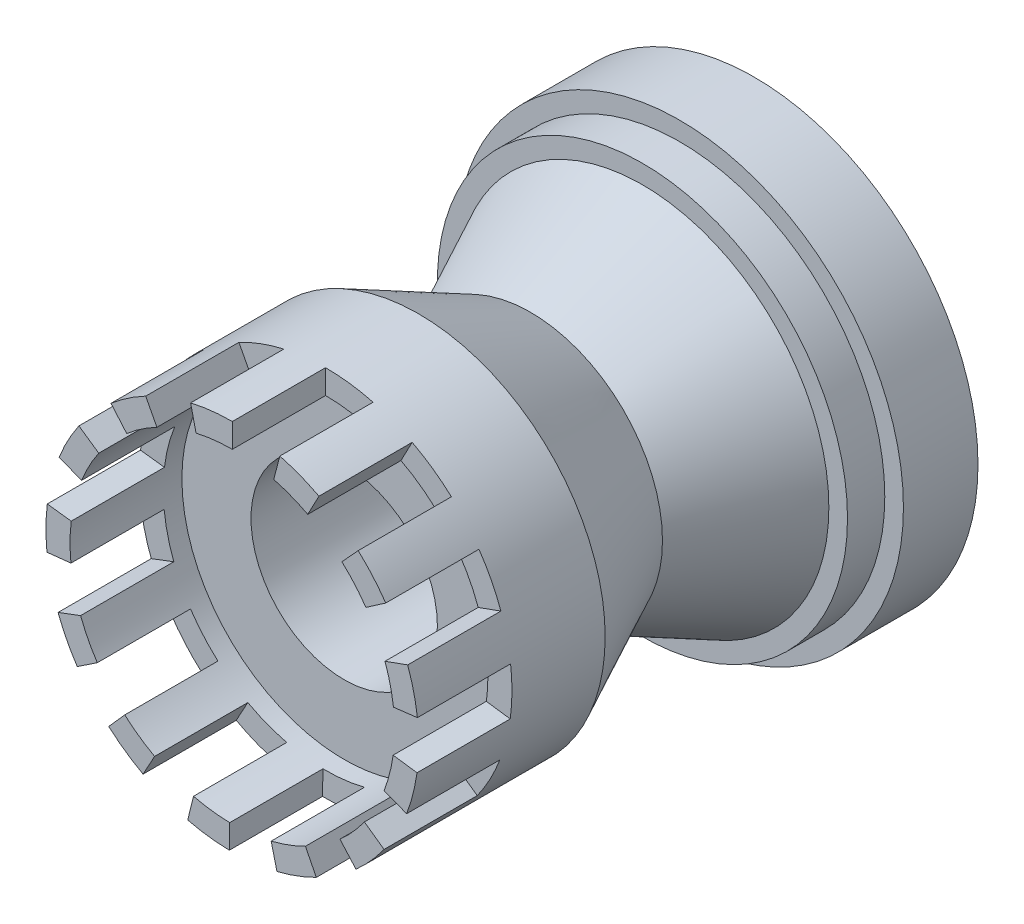
SolidWorks part; units mm, degrees
ref_plane "정면" through (0, 0, 0) normal (0, 0, 1) x (1, 0, 0)
ref_plane "윗면" through (0, 0, 0) normal (0, 1, 0) x (1, 0, 0)
ref_plane "우측면" through (0, 0, 0) normal (1, 0, 0) x (0, 0, -1)
sketch "스케치1" plane through (0, 0, 0) normal (0, 0, 1) x (1, 0, 0)
  circle A0 centre (0, 0) radius 6
  dimension "D1" = 12
extrude "보스-돌출1" add sketch "스케치1" along normal blind 2
sketch "스케치2" plane through (0, 0, 2) normal (0, 0, 1) x (1, 0, 0)
  circle A0 centre (0, 0) radius 5.5
  dimension "D1" = 11
extrude "보스-돌출2" add sketch "스케치2" along normal blind 1
sketch "스케치3" plane through (0, 0, 3) normal (0, 0, 1) x (1, 0, 0)
  circle A0 centre (0, 0) radius 5
  dimension "D1" = 10
extrude "보스-돌출3" add sketch "스케치3" along normal blind 3 draft 26
sketch "스케치4" plane through (0, 0, 6) normal (0, 0, 1) x (1, 0, 0)
  circle A0 centre (0, 0) radius 3.5368
extrude "보스-돌출4" add sketch "스케치4" along normal blind 3 draft 26 draft outward yes
sketch "스케치5" plane through (0, 0, 9) normal (0, 0, 1) x (1, 0, 0)
  circle A0 centre (0, 0) radius 5
extrude "보스-돌출5" add sketch "스케치5" along normal blind 5
sketch "스케치6" plane through (0, 0, 14) normal (0, 0, 1) x (1, 0, 0)
  circle A0 centre (0, 0) radius 4.3531
extrude "컷-돌출1" cut sketch "스케치6" against normal blind 3
sketch "스케치7" plane through (0, 0, 14) normal (0, 0, 1) x (1, 0, 0)
  line L0 (0, 0) -> (0, 4.3531) construction
  line L1 (0, 4.3531) -> (0, 5)
  line L2 (0, 0) -> (1.1097, 4.2093) construction
  line L3 (1.1097, 4.2093) -> (1.2747, 4.8348)
  line L4 (2.023, 3.8545) -> (2.3236, 4.4273)
  line L5 (2.9388, 3.2114) -> (3.3755, 3.6886)
  line L6 (3.5825, 2.4728) -> (4.1149, 2.8403)
  line L7 (4.0946, 1.4778) -> (4.7031, 1.6974)
  line L8 (4.3213, 0.5247) -> (4.9635, 0.6027)
  line L9 (4.3123, -0.5943) -> (4.9532, -0.6826)
  line L10 (4.0702, -1.5436) -> (4.6751, -1.773)
  line L11 (3.5422, -2.5303) -> (4.0686, -2.9063)
  line L12 (2.8866, -3.2583) -> (3.3156, -3.7426)
  line L13 (1.9606, -3.8866) -> (2.252, -4.4642)
  line L14 (1.0418, -4.2266) -> (1.1966, -4.8547)
  line L15 (-0.0702, -4.3525) -> (-0.0806, -4.9994)
  line L16 (-1.0418, -4.2266) -> (-1.1966, -4.8547)
  line L17 (-2.0848, -3.8214) -> (-2.3947, -4.3893)
  line L18 (-2.8866, -3.2583) -> (-3.3156, -3.7426)
  line L19 (-3.6219, -2.4148) -> (-4.1602, -2.7736)
  line L20 (-4.0702, -1.5436) -> (-4.6751, -1.773)
  line L21 (-4.3292, -0.455) -> (-4.9726, -0.5226)
  line L22 (-4.3213, 0.5247) -> (-4.9635, 0.6027)
  line L23 (-4.0448, 1.609) -> (-4.6459, 1.8481)
  line L24 (-3.5825, 2.4728) -> (-4.1149, 2.8403)
  line L25 (-2.8337, 3.3044) -> (-3.2549, 3.7955)
  line L26 (-2.023, 3.8545) -> (-2.3236, 4.4273)
  line L27 (-0.9735, 4.2428) -> (-1.1182, 4.8734)
  circle A0 centre (0, 0) radius 4.3531 construction
  circle A1 centre (0, 0) radius 5 construction
  circle A2 centre (0, 0) radius 5 construction
  arc A3 (1.1097, 4.2093) -> (0, 4.3531) centre (0, 0) ccw
  arc A4 (1.2747, 4.8348) -> (0, 5) centre (0, 0) ccw
  arc A5 (3.3755, 3.6886) -> (2.3236, 4.4273) centre (0, 0) ccw
  arc A6 (2.9388, 3.2114) -> (2.023, 3.8545) centre (0, 0) ccw
  arc A7 (4.7031, 1.6974) -> (4.1149, 2.8403) centre (0, 0) ccw
  arc A8 (4.0946, 1.4778) -> (3.5825, 2.4728) centre (0, 0) ccw
  arc A9 (4.9532, -0.6826) -> (4.9635, 0.6027) centre (0, 0) ccw
  arc A10 (4.3123, -0.5943) -> (4.3213, 0.5247) centre (0, 0) ccw
  arc A11 (4.0686, -2.9063) -> (4.6751, -1.773) centre (0, 0) ccw
  arc A12 (3.5422, -2.5303) -> (4.0702, -1.5436) centre (0, 0) ccw
  arc A13 (2.252, -4.4642) -> (3.3156, -3.7426) centre (0, 0) ccw
  arc A14 (1.9606, -3.8866) -> (2.8866, -3.2583) centre (0, 0) ccw
  arc A15 (-0.0806, -4.9994) -> (1.1966, -4.8547) centre (0, 0) ccw
  arc A16 (-0.0702, -4.3525) -> (1.0418, -4.2266) centre (0, 0) ccw
  arc A17 (-2.3947, -4.3893) -> (-1.1966, -4.8547) centre (0, 0) ccw
  arc A18 (-2.0848, -3.8214) -> (-1.0418, -4.2266) centre (0, 0) ccw
  arc A19 (-4.1602, -2.7736) -> (-3.3156, -3.7426) centre (0, 0) ccw
  arc A20 (-3.6219, -2.4148) -> (-2.8866, -3.2583) centre (0, 0) ccw
  arc A21 (-4.9726, -0.5226) -> (-4.6751, -1.773) centre (0, 0) ccw
  arc A22 (-4.3292, -0.455) -> (-4.0702, -1.5436) centre (0, 0) ccw
  arc A23 (-4.6459, 1.8481) -> (-4.9635, 0.6027) centre (0, 0) ccw
  arc A24 (-4.0448, 1.609) -> (-4.3213, 0.5247) centre (0, 0) ccw
  arc A25 (-3.2549, 3.7955) -> (-4.1149, 2.8403) centre (0, 0) ccw
  arc A26 (-2.8337, 3.3044) -> (-3.5825, 2.4728) centre (0, 0) ccw
  arc A27 (-1.1182, 4.8734) -> (-2.3236, 4.4273) centre (0, 0) ccw
  arc A28 (-0.9735, 4.2428) -> (-2.023, 3.8545) centre (0, 0) ccw
  point P64 (0, 0)
  dimension "D1" = 13
extrude "컷-돌출2" cut sketch "스케치7" against normal blind 2.5
sketch "스케치8" plane through (0, 0, 11) normal (0, 0, 1) x (1, 0, 0)
  circle A0 centre (0, 0) radius 2.5
  dimension "D1" = 5
extrude "컷-돌출3" cut sketch "스케치8" against normal through all
